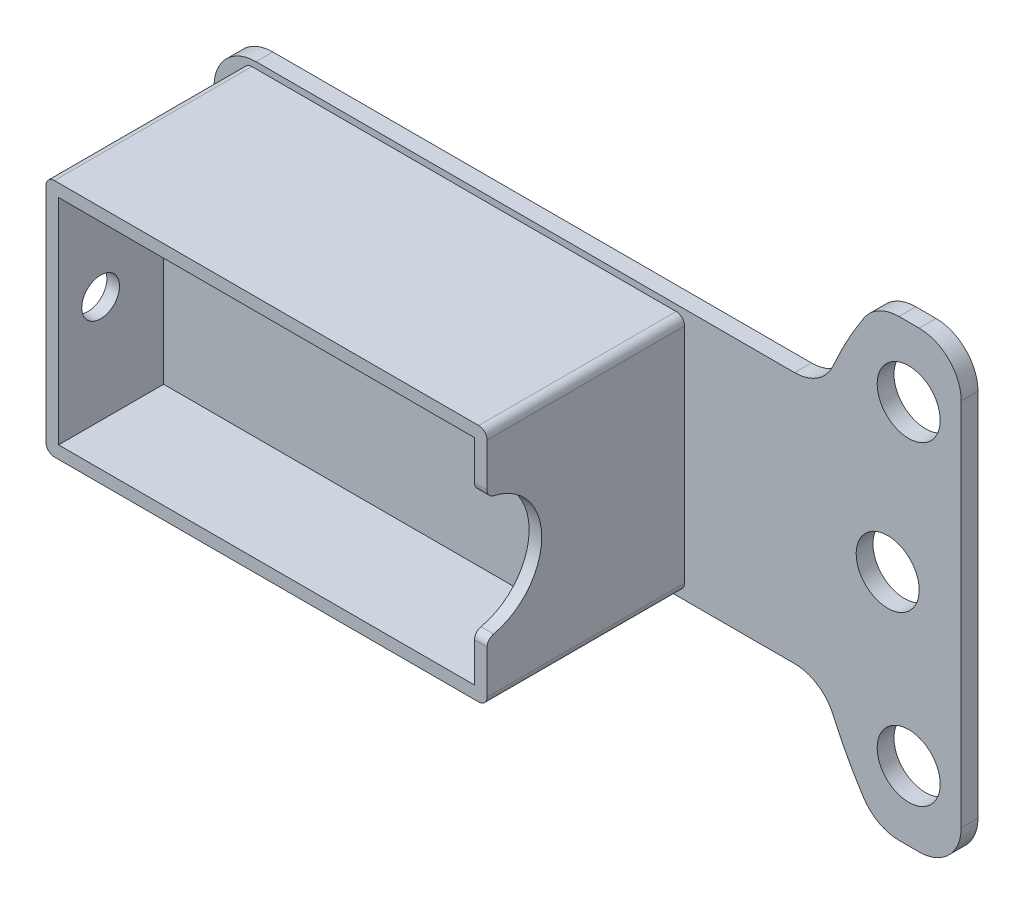
SolidWorks part; units mm, degrees
ref_plane "Plano frontal" through (0, 0, 0) normal (0, 0, 1) x (1, 0, 0)
ref_plane "Plano superior" through (0, 0, 0) normal (0, 1, 0) x (1, 0, 0)
ref_plane "Plano direito" through (0, 0, 0) normal (1, 0, 0) x (0, 0, -1)
sketch "Esboço1" plane through (0, 0, 0) normal (0, 0, 1) x (1, 0, 0)
  line L1 (-72, -54) -> (-52, -54)
  line L2 (-52, -54) -> (-52, 54)
  line L3 (-52, 54) -> (-72, 54)
  arc A0 (-72, 54) -> (-72, -54) centre (0, 0) ccw
  dimension "D1" = 180
  dimension "D2" = 108
  dimension "D3" = 20
extrude "Ressalto-extrusão1" add sketch "Esboço1" along normal blind 4
sketch "Esboço2" plane through (0, 0, 0) normal (0, 0, -1) x (-1, 0, 0)
  line L0 (52, 0) -> (69.5, 0)
  line L1 (52, -54) -> (52, 54) construction
  line L2 (52, -54) -> (64.5, -54)
  line L3 (72, -54) -> (52, -54) construction
  line L4 (64.5, -54) -> (64.5, -37.5)
  circle A0 centre (69.5, 0) radius 7.5
  circle A1 centre (64.5, -37.5) radius 7.5
  circle A2 centre (64.5, 37.5) radius 7.5
  dimension "D2" = 15
  dimension "D5" = 15
  dimension "D1" = 17.5
  dimension "D3" = 12.5
  dimension "D4" = 16.5
extrude "Corte-extrusão1" cut sketch "Esboço2" against normal blind 10
sketch "Esboço3" plane through (0, 0, 0) normal (0, 0, 1) x (1, 0, 0)
  line L0 (-90, 0) -> (-52, 0) construction
  line L1 (-52, -54) -> (-52, 54) construction
  line L2 (-84.8528, -30) -> (-84.8528, 30)
  line L3 (-84.8528, 30) -> (-229.8528, 30)
  line L4 (-229.8528, 30) -> (-229.8528, -30)
  line L5 (-84.8528, -30) -> (-229.8528, -30)
  arc A0 (-72, 54) -> (-72, -54) centre (0, 0) ccw construction
  point P12 (-229.8528, 0)
  point P13 (-84.8528, 0)
  dimension "D1" = 30
  dimension "D2" = 145
extrude "Ressalto-extrusão3" add sketch "Esboço3" along normal blind 4
sketch "Esboço4" plane through (0, 0, 4) normal (0, 0, 1) x (1, 0, 0)
  line L0 (-229.8528, 0) -> (-219.8528, 0)
  line L1 (-229.8528, 30) -> (-229.8528, -30) construction
  line L2 (-219.8528, 0) -> (-219.8528, 25.5)
  line L3 (-229.8528, 0) -> (-52, 0) construction
  line L4 (-52, -54) -> (-52, 54) construction
  line L5 (-219.8528, 25.5) -> (-120.8528, 25.5)
  line L6 (-120.8528, 25.5) -> (-120.8528, 0)
  line L7 (-222.8528, 0) -> (-222.8528, 28.5)
  line L8 (-222.8528, 28.5) -> (-117.8528, 28.5)
  line L9 (-117.8528, 28.5) -> (-117.8528, 0)
  line L10 (-219.8528, 0) -> (-219.8528, -25.5)
  line L11 (-222.8528, 0) -> (-222.8528, -28.5)
  line L12 (-222.8528, -28.5) -> (-117.8528, -28.5)
  line L13 (-219.8528, -25.5) -> (-120.8528, -25.5)
  line L14 (-117.8528, -28.5) -> (-117.8528, 0)
  line L15 (-120.8528, -25.5) -> (-120.8528, 0)
  dimension "D1" = 10
  dimension "D2" = 25.5
  dimension "D3" = 99
  dimension "D4" = 3
extrude "Ressalto-extrusão4" add sketch "Esboço4" along normal blind 47 contours L3 L15 L13 L10 L0 L11 L12 L14 | L6 L3 L9 L8 L7 L0 L2 L5
sketch "Esboço5" plane through (-117.8528, 0, 0) normal (1, 0, 0) x (0, 0, -1)
  line L0 (-51, -28.5) -> (-51, -14.5) construction
  line L1 (-51, -28.5) -> (-51, 28.5) construction
  line L2 (-51, 0) -> (-4, 0) construction
  line L3 (-4, -28.5) -> (-4, 28.5) construction
  line L4 (-51, 28.5) -> (-51, 14.5) construction
  line L6 (-4, 0) -> (-38, 0)
  line L7 (-51, -14.5) -> (-51, 14.5)
  arc A2 (-51, -14.5) -> (-51, 14.5) centre (-52.5865, 0) ccw
  line M7 (-51, 28.5) -> (-51, -28.5)
  dimension "D1" = 14
  dimension "D2" = 34
extrude "Corte-extrusão3" cut sketch "Esboço5" against normal blind 10 contours A2 M7
sketch "Esboço6" plane through (-222.8528, 0, 0) normal (-1, 0, 0) x (0, 0, 1)
  line L0 (4, 0) -> (41, 0)
  line L1 (4, 30) -> (4, -30) construction
  circle A0 centre (41, 0) radius 4.5
  dimension "D2" = 9
  dimension "D1" = 37
extrude "Corte-extrusão4" cut sketch "Esboço6" against normal blind 9
fillet "Filete1" radius 10 2 edges at (-229.8528, 30, 2) (-229.8528, -30, 2)
fillet "Filete3" radius 10 6 edges at (-72, 54, 2) (-72, -54, 2) (-52, 54, 2) (-52, -54, 2) (-84.8528, 30, 2) (-84.8528, -30, 2)
fillet "Filete4" radius 2 6 edges at (-117.8528, 28.5, 27.5) (-222.8528, 28.5, 27.5) (-222.8528, -28.5, 27.5) (-117.8528, -28.5, 27.5) (-119.3528, -14.5, 51) (-119.3528, 14.5, 51)
sketch "Esboço7" plane through (0, 0, 4) normal (0, 0, 1) x (1, 0, 0)
  line L0 (-219.8528, 25.5) -> (-120.8528, 25.5) construction
  line L1 (-219.8528, 25.5) -> (-120.8528, 25.5)
  line L2 (-219.8528, 25.5) -> (-219.8528, -25.5) construction
  line L3 (-219.8528, 25.5) -> (-219.8528, -25.5)
  line L4 (-219.8528, -25.5) -> (-120.8528, -25.5) construction
  line L5 (-219.8528, -25.5) -> (-120.8528, -25.5)
  line L6 (-120.8528, -25.5) -> (-120.8528, 25.5) construction
  line L7 (-120.8528, -25.5) -> (-120.8528, 25.5)
extrude "Ressalto-extrusão5" add sketch "Esboço7" along normal blind 22
